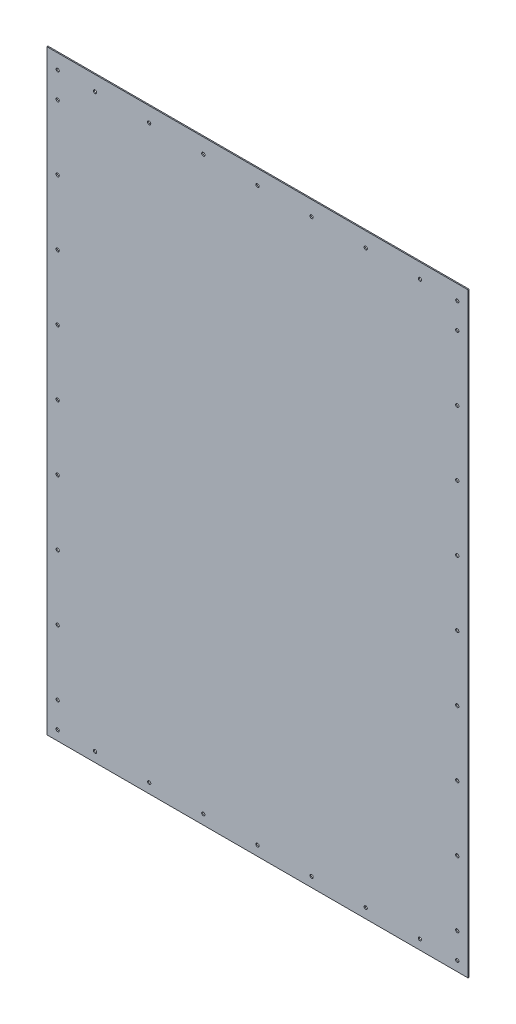
SolidWorks part; units mm, degrees
material "Nikiel"
ref_plane "Płaszczyzna przednia" through (0, 0, 0) normal (0, 0, 1) x (1, 0, 0)
ref_plane "Płaszczyzna górna" through (0, 0, 0) normal (0, 1, 0) x (1, 0, 0)
ref_plane "Płaszczyzna prawa" through (0, 0, 0) normal (1, 0, 0) x (0, 0, -1)
sketch "Szkic1" plane through (0, 0, 0) normal (0, 0, 1) x (1, 0, 0)
  line L1 (-86.2801, 49.1786) -> (55.5484, 49.1786)
  line L2 (-86.2801, 49.1786) -> (-86.2801, -28.7786)
  line L3 (-86.2801, -28.7786) -> (55.5484, -28.7786)
  line L4 (55.5484, 49.1786) -> (55.5484, -28.7786)
extrude "Dodanie-wyciągnięcie1" add sketch "Szkic1" along normal blind 1
sketch "Szkic2" plane through (-86.2801, 0, 0) normal (-1, 0, 0) x (0, 0, 1)
  line L1 (0, 49.1786) -> (1, 49.1786)
  line L2 (0, 49.1786) -> (0, -28.7786)
  line L3 (0, -28.7786) -> (1, -28.7786)
  line L4 (1, 49.1786) -> (1, -28.7786)
extrude "Dodanie-wyciągnięcie2" add sketch "Szkic2" along normal up to surface (247.1714 mm away)
sketch "Szkic3" plane through (0, -28.7786, 0) normal (0, -1, 0) x (1, 0, 0)
  line L1 (55.5484, 1) -> (-333.4516, 1)
  line L2 (55.5484, 1) -> (55.5484, 0)
  line L3 (55.5484, 0) -> (-333.4516, 0)
  line L4 (-333.4516, 1) -> (-333.4516, 0)
extrude "Dodanie-wyciągnięcie3" add sketch "Szkic3" along normal up to surface (472.3582 mm away)
sketch "Szkic4" plane through (0, 0, 1) normal (0, 0, 1) x (1, 0, 0)
  circle A1 centre (-323.4516, 35.4015) radius 1.5
  circle A2 centre (45.5484, 35.4015) radius 1.5
  circle A3 centre (45.5484, -492.1368) radius 1.5
  circle A4 centre (-323.4516, -492.1368) radius 1.5
  circle A5 centre (-323.4516, -228.3677) radius 1.5
  circle A6 centre (45.5484, -228.3677) radius 1.5
  circle A7 centre (-138.9516, 35.4015) radius 1.5
  circle A8 centre (-138.9516, -492.1368) radius 1.5
  circle A9 centre (-323.4516, -168.3677) radius 1.5
  circle A10 centre (-323.4516, -108.3677) radius 1.5
  circle A11 centre (-323.4516, -48.3677) radius 1.5
  circle A12 centre (-323.4516, 11.6323) radius 1.5
  circle A13 centre (-323.4516, -468.3677) radius 1.5
  circle A14 centre (-323.4516, -408.3677) radius 1.5
  circle A15 centre (-323.4516, -348.3677) radius 1.5
  circle A16 centre (-323.4516, -288.3677) radius 1.5
  circle A17 centre (-88.9516, -492.1368) radius 1.5
  circle A18 centre (-88.9516, 35.4015) radius 1.5
  circle A19 centre (-38.9516, -492.1368) radius 1.5
  circle A20 centre (-38.9516, 35.4015) radius 1.5
  circle A21 centre (11.0484, -492.1368) radius 1.5
  circle A22 centre (11.0484, 35.4015) radius 1.5
  circle A23 centre (-288.9516, 35.4015) radius 1.5
  circle A24 centre (-238.9516, 35.4015) radius 1.5
  circle A25 centre (-188.9516, 35.4015) radius 1.5
  circle A26 centre (-288.9516, -492.1368) radius 1.5
  circle A27 centre (-238.9516, -492.1368) radius 1.5
  circle A28 centre (-188.9516, -492.1368) radius 1.5
  circle A29 centre (45.5484, -288.3677) radius 1.5
  circle A30 centre (45.5484, -348.3677) radius 1.5
  circle A31 centre (45.5484, -408.3677) radius 1.5
  circle A32 centre (45.5484, -468.3677) radius 1.5
  circle A33 centre (45.5484, 11.6323) radius 1.5
  circle A34 centre (45.5484, -48.3677) radius 1.5
  circle A35 centre (45.5484, -108.3677) radius 1.5
  circle A36 centre (45.5484, -168.3677) radius 1.5
  circle A37 centre (45.5484, -228.3677) radius 1.5
  dimension "D1" = 5
  dimension "D2" = 4
extrude "Wytnij-wyciągnięcie1" cut sketch "Szkic4" against normal blind 10 contours A31 | A8 | A4 | A13 | A14 | A15 | A16 | A5 | A9 | A10 | A11 | A12 | A1 | A23 | A24 | A25 | A7 | A18 | A20 | A22 | A2 | A33 | A34 | A35 | A36 | A6 | A29 | A30 | A32 | A3 | A21 | A19 | A17 | A28 | A27 | A26
